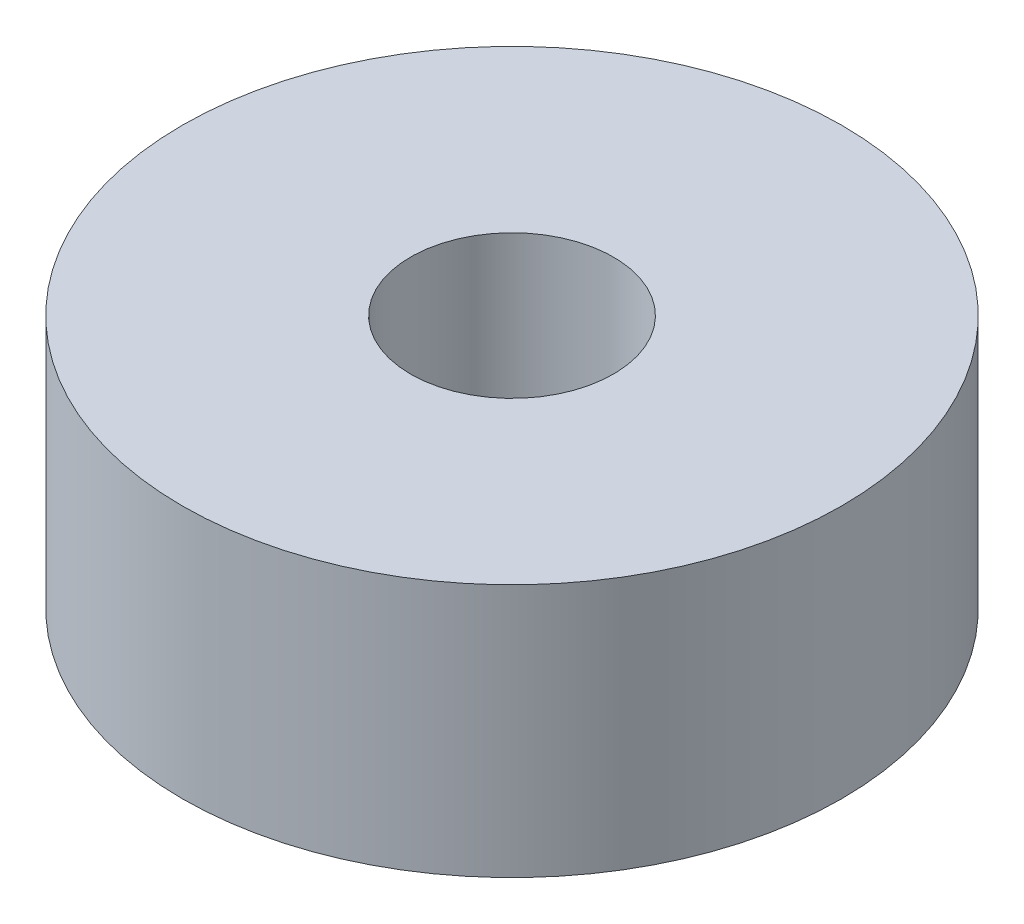
SolidWorks part; units mm, degrees
ref_plane "Front" through (0, 0, 0) normal (0, 0, 1) x (1, 0, 0)
ref_plane "Top" through (0, 0, 0) normal (0, 1, 0) x (1, 0, 0)
ref_plane "Right" through (0, 0, 0) normal (1, 0, 0) x (0, 0, -1)
sketch "Sketch1" plane through (0, 0, 0) normal (0, 1, 0) x (1, 0, 0)
  circle A0 centre (0, 0) radius 6.5
  circle A1 centre (0, 0) radius 2
  dimension "D1" = 13
  dimension "D2" = 4
extrude "Boss-Extrude3" add sketch "Sketch1" along normal blind 5
